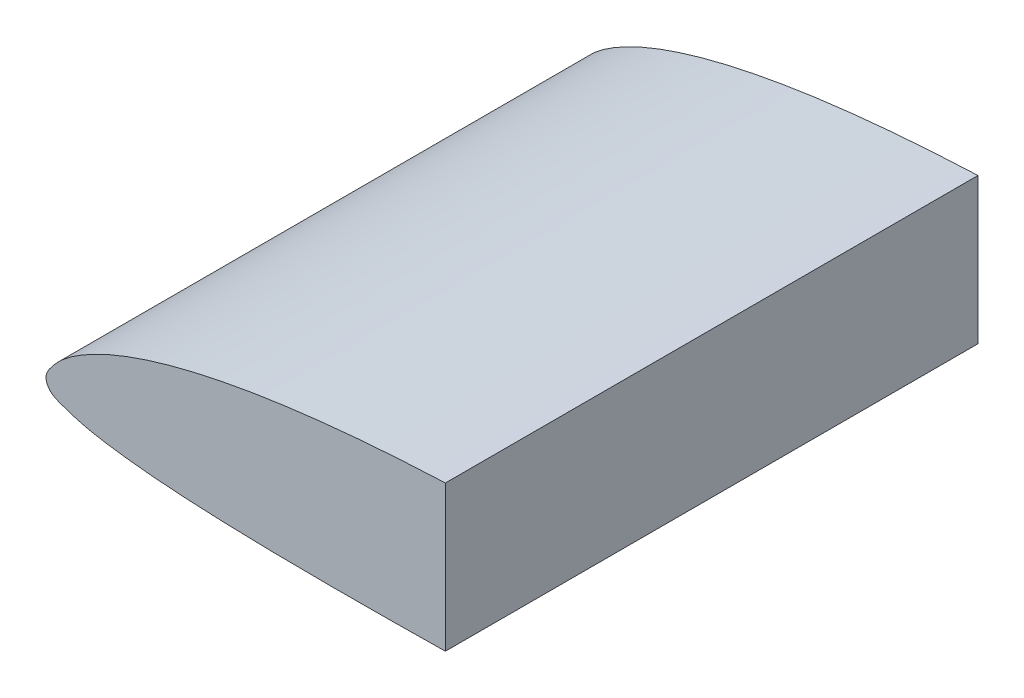
SolidWorks part; units mm, degrees
ref_plane "Front Plane" through (0, 0, 0) normal (0, 0, 1) x (1, 0, 0)
ref_plane "Top Plane" through (0, 0, 0) normal (0, 1, 0) x (1, 0, 0)
ref_plane "Right Plane" through (0, 0, 0) normal (1, 0, 0) x (0, 0, -1)
curve "Curve1"
  spline degree 3 poles (302.6596, 0.1157, 0) (305.3381, -0.0423, 0) (302.669, 0.2207, 0) (300.522, 0.5446, 0) (295.3689, 1.2875, 0) (289.1609, 2.3365, 0) (281.2138, 3.7195, 0) (272.0211, 5.3425, 0) (261.6111, 7.1258, 0) (250.1482, 8.9723, 0) (237.7292, 10.7955, 0) (224.4667, 12.5459, 0) (210.487, 14.2121, 0) (195.9393, 15.7786, 0) (180.9854, 17.2135, 0) (165.7905, 18.4813, 0) (150.5173, 19.555, 0) (135.3259, 20.3976, 0) (120.3737, 20.9834, 0) (105.8119, 21.2902, 0) (91.7835, 21.2891, 0) (78.4214, 20.9725, 0) (65.8465, 20.3288, 0) (54.1674, 19.3419, 0) (43.4744, 18.033, 0) (33.8487, 16.4082, 0) (25.3526, 14.4995, 0) (18.0396, 12.3489, 0) (11.9314, 10.004, 0) (7.0881, 7.5397, 0) (3.4097, 5.063, 0) (1.1505, 2.6895, 0) (-0.3415, 0.4062, 0) (0.6752, -2.0035, 0) (3.5859, -3.0935, 0) (7.5885, -4.3543, 0) (13.2868, -5.2878, 0) (20.4322, -6.0839, 0) (29.0602, -6.6397, 0) (39.0679, -6.9954, 0) (50.3738, -7.1553, 0) (62.8573, -7.1477, 0) (76.3839, -6.9932, 0) (90.8032, -6.6986, 0) (105.9568, -6.2837, 0) (121.6773, -5.7705, 0) (137.79, -5.1759, 0) (154.1149, -4.5178, 0) (170.47, -3.8155, 0) (186.6709, -3.1003, 0) (202.5321, -2.3909, 0) (217.8684, -1.7248, 0) (232.4928, -1.115, 0) (246.2209, -0.6139, 0) (258.8615, -0.2157, 0) (270.2531, 0.0554, 0) (280.189, 0.2196, 0) (288.6505, 0.2748, 0) (295.1556, 0.2617, 0) (300.4646, 0.1437, 0) (302.6596, 0.1157, 0) (305.3381, -0.0423, 0) (302.669, 0.2207, 0) knots -0.014411 -0.006469 -0.001624 0 0.001633 0.006456 0.014273 0.024844 0.037882 0.053108 0.070262 0.089112 0.109474 0.131183 0.154044 0.177808 0.202202 0.22696 0.251816 0.276516 0.300807 0.324444 0.347208 0.368894 0.389314 0.408315 0.425773 0.441588 0.45568 0.468012 0.478567 0.487363 0.494419 0.499795 0.503598 0.50652 0.511061 0.517924 0.527205 0.538874 0.552882 0.569133 0.587486 0.607759 0.629726 0.653145 0.677762 0.703306 0.729491 0.756024 0.782609 0.80895 0.834737 0.859675 0.88346 0.905785 0.926349 0.944858 0.961055 0.974701 0.985589 0.993531 0.998376 1 1.001633 1.006456 1.014273 periodic
sketch "Sketch1" plane through (0, 0, 0) normal (0, 0, 1) x (1, 0, 0)
  line L2 (0, 0) -> (0, 1.9929) construction
  spline S1 degree 3 poles (302.6596, 0.1157) (305.3381, -0.0423) (302.669, 0.2207) (300.522, 0.5446) (295.3689, 1.2875) (289.1609, 2.3365) (281.2138, 3.7195) (272.0211, 5.3425) (261.6111, 7.1258) (250.1482, 8.9723) (237.7292, 10.7955) (224.4667, 12.5459) (210.487, 14.2121) (195.9393, 15.7786) (180.9854, 17.2135) (165.7905, 18.4813) (150.5173, 19.555) (135.3259, 20.3976) (120.3737, 20.9834) (105.8119, 21.2902) (91.7835, 21.2891) (78.4214, 20.9725) (65.8465, 20.3288) (54.1674, 19.3419) (43.4744, 18.033) (33.8487, 16.4082) (25.3526, 14.4995) (18.0396, 12.3489) (11.9314, 10.004) (7.0881, 7.5397) (3.4097, 5.063) (1.1505, 2.6895) (-0.3415, 0.4062) (0.6752, -2.0035) (3.5859, -3.0935) (7.5885, -4.3543) (13.2868, -5.2878) (20.4322, -6.0839) (29.0602, -6.6397) (39.0679, -6.9954) (50.3738, -7.1553) (62.8573, -7.1477) (76.3839, -6.9932) (90.8032, -6.6986) (105.9568, -6.2837) (121.6773, -5.7705) (137.79, -5.1759) (154.1149, -4.5178) (170.47, -3.8155) (186.6709, -3.1003) (202.5321, -2.3909) (217.8684, -1.7248) (232.4928, -1.115) (246.2209, -0.6139) (258.8615, -0.2157) (270.2531, 0.0554) (280.189, 0.2196) (288.6505, 0.2748) (295.1556, 0.2617) (300.4646, 0.1437) (302.6596, 0.1157) (305.3381, -0.0423) (302.669, 0.2207) knots -0.014411 -0.006469 -0.001624 0 0.001633 0.006456 0.014273 0.024844 0.037882 0.053108 0.070262 0.089112 0.109474 0.131183 0.154044 0.177808 0.202202 0.22696 0.251816 0.276516 0.300807 0.324444 0.347208 0.368894 0.389314 0.408315 0.425773 0.441588 0.45568 0.468012 0.478567 0.487363 0.494419 0.499795 0.503598 0.50652 0.511061 0.517924 0.527205 0.538874 0.552882 0.569133 0.587486 0.607759 0.629726 0.653145 0.677762 0.703306 0.729491 0.756024 0.782609 0.80895 0.834737 0.859675 0.88346 0.905785 0.926349 0.944858 0.961055 0.974701 0.985589 0.993531 0.998376 1 1.001633 1.006456 1.014273 only from (304.8, 0) to (304.8, 0) construction
  spline S2 degree 3 poles (302.6596, 0.1157) (305.3381, -0.0423) (302.669, 0.2207) (300.522, 0.5446) (295.3689, 1.2875) (289.1609, 2.3365) (281.2138, 3.7195) (272.0211, 5.3425) (261.6111, 7.1258) (250.1482, 8.9723) (237.7292, 10.7955) (224.4667, 12.5459) (210.487, 14.2121) (195.9393, 15.7786) (180.9854, 17.2135) (165.7905, 18.4813) (150.5173, 19.555) (135.3259, 20.3976) (120.3737, 20.9834) (105.8119, 21.2902) (91.7835, 21.2891) (78.4214, 20.9725) (65.8465, 20.3288) (54.1674, 19.3419) (43.4744, 18.033) (33.8487, 16.4082) (25.3526, 14.4995) (18.0396, 12.3489) (11.9314, 10.004) (7.0881, 7.5397) (3.4097, 5.063) (1.1505, 2.6895) (-0.3415, 0.4062) (0.6752, -2.0035) (3.5859, -3.0935) (7.5885, -4.3543) (13.2868, -5.2878) (20.4322, -6.0839) (29.0602, -6.6397) (39.0679, -6.9954) (50.3738, -7.1553) (62.8573, -7.1477) (76.3839, -6.9932) (90.8032, -6.6986) (105.9568, -6.2837) (121.6773, -5.7705) (137.79, -5.1759) (154.1149, -4.5178) (170.47, -3.8155) (186.6709, -3.1003) (202.5321, -2.3909) (217.8684, -1.7248) (232.4928, -1.115) (246.2209, -0.6139) (258.8615, -0.2157) (270.2531, 0.0554) (280.189, 0.2196) (288.6505, 0.2748) (295.1556, 0.2617) (300.4646, 0.1437) (302.6596, 0.1157) (305.3381, -0.0423) (302.669, 0.2207) knots -0.014411 -0.006469 -0.001624 0 0.001633 0.006456 0.014273 0.024844 0.037882 0.053108 0.070262 0.089112 0.109474 0.131183 0.154044 0.177808 0.202202 0.22696 0.251816 0.276516 0.300807 0.324444 0.347208 0.368894 0.389314 0.408315 0.425773 0.441588 0.45568 0.468012 0.478567 0.487363 0.494419 0.499795 0.503598 0.50652 0.511061 0.517924 0.527205 0.538874 0.552882 0.569133 0.587486 0.607759 0.629726 0.653145 0.677762 0.703306 0.729491 0.756024 0.782609 0.80895 0.834737 0.859675 0.88346 0.905785 0.926349 0.944858 0.961055 0.974701 0.985589 0.993531 0.998376 1 1.001633 1.006456 1.014273 only from (304.8, 0) to (304.8, 0)
extrude "Boss-Extrude1" add sketch "Sketch1" along normal blind 101.6
sketch "Sketch2" plane through (0, 0, 101.6) normal (0, 0, 1) x (1, 0, 0)
  line L0 (76.2, 20.8248) -> (76.2, -6.975)
  spline S0 degree 3 poles (302.6596, 0.1157) (305.3381, -0.0423) (302.669, 0.2207) (300.522, 0.5446) (295.3689, 1.2875) (289.1609, 2.3365) (281.2138, 3.7195) (272.0211, 5.3425) (261.6111, 7.1258) (250.1482, 8.9723) (237.7292, 10.7955) (224.4667, 12.5459) (210.487, 14.2121) (195.9393, 15.7786) (180.9854, 17.2135) (165.7905, 18.4813) (150.5173, 19.555) (135.3259, 20.3976) (120.3737, 20.9834) (105.8119, 21.2902) (91.7835, 21.2891) (78.4214, 20.9725) (65.8465, 20.3288) (54.1674, 19.3419) (43.4744, 18.033) (33.8487, 16.4082) (25.3526, 14.4995) (18.0396, 12.3489) (11.9314, 10.004) (7.0881, 7.5397) (3.4097, 5.063) (1.1505, 2.6895) (-0.3415, 0.4062) (0.6752, -2.0035) (3.5859, -3.0935) (7.5885, -4.3543) (13.2868, -5.2878) (20.4322, -6.0839) (29.0602, -6.6397) (39.0679, -6.9954) (50.3738, -7.1553) (62.8573, -7.1477) (76.3839, -6.9932) (90.8032, -6.6986) (105.9568, -6.2837) (121.6773, -5.7705) (137.79, -5.1759) (154.1149, -4.5178) (170.47, -3.8155) (186.6709, -3.1003) (202.5321, -2.3909) (217.8684, -1.7248) (232.4928, -1.115) (246.2209, -0.6139) (258.8615, -0.2157) (270.2531, 0.0554) (280.189, 0.2196) (288.6505, 0.2748) (295.1556, 0.2617) (300.4646, 0.1437) (302.6596, 0.1157) (305.3381, -0.0423) (302.669, 0.2207) knots -0.014411 -0.006469 -0.001624 0 0.001633 0.006456 0.014273 0.024844 0.037882 0.053108 0.070262 0.089112 0.109474 0.131183 0.154044 0.177808 0.202202 0.22696 0.251816 0.276516 0.300807 0.324444 0.347208 0.368894 0.389314 0.408315 0.425773 0.441588 0.45568 0.468012 0.478567 0.487363 0.494419 0.499795 0.503598 0.50652 0.511061 0.517924 0.527205 0.538874 0.552882 0.569133 0.587486 0.607759 0.629726 0.653145 0.677762 0.703306 0.729491 0.756024 0.782609 0.80895 0.834737 0.859675 0.88346 0.905785 0.926349 0.944858 0.961055 0.974701 0.985589 0.993531 0.998376 1 1.001633 1.006456 1.014273 only from (304.8, 0) to (304.8, 0) construction
  spline S1 degree 3 poles (302.6596, 0.1157) (305.3381, -0.0423) (302.669, 0.2207) (300.522, 0.5446) (295.3689, 1.2875) (289.1609, 2.3365) (281.2138, 3.7195) (272.0211, 5.3425) (261.6111, 7.1258) (250.1482, 8.9723) (237.7292, 10.7955) (224.4667, 12.5459) (210.487, 14.2121) (195.9393, 15.7786) (180.9854, 17.2135) (165.7905, 18.4813) (150.5173, 19.555) (135.3259, 20.3976) (120.3737, 20.9834) (105.8119, 21.2902) (91.7835, 21.2891) (78.4214, 20.9725) (65.8465, 20.3288) (54.1674, 19.3419) (43.4744, 18.033) (33.8487, 16.4082) (25.3526, 14.4995) (18.0396, 12.3489) (11.9314, 10.004) (7.0881, 7.5397) (3.4097, 5.063) (1.1505, 2.6895) (-0.3415, 0.4062) (0.6752, -2.0035) (3.5859, -3.0935) (7.5885, -4.3543) (13.2868, -5.2878) (20.4322, -6.0839) (29.0602, -6.6397) (39.0679, -6.9954) (50.3738, -7.1553) (62.8573, -7.1477) (76.3839, -6.9932) (90.8032, -6.6986) (105.9568, -6.2837) (121.6773, -5.7705) (137.79, -5.1759) (154.1149, -4.5178) (170.47, -3.8155) (186.6709, -3.1003) (202.5321, -2.3909) (217.8684, -1.7248) (232.4928, -1.115) (246.2209, -0.6139) (258.8615, -0.2157) (270.2531, 0.0554) (280.189, 0.2196) (288.6505, 0.2748) (295.1556, 0.2617) (300.4646, 0.1437) (302.6596, 0.1157) (305.3381, -0.0423) (302.669, 0.2207) knots -0.014411 -0.006469 -0.001624 0 0.001633 0.006456 0.014273 0.024844 0.037882 0.053108 0.070262 0.089112 0.109474 0.131183 0.154044 0.177808 0.202202 0.22696 0.251816 0.276516 0.300807 0.324444 0.347208 0.368894 0.389314 0.408315 0.425773 0.441588 0.45568 0.468012 0.478567 0.487363 0.494419 0.499795 0.503598 0.50652 0.511061 0.517924 0.527205 0.538874 0.552882 0.569133 0.587486 0.607759 0.629726 0.653145 0.677762 0.703306 0.729491 0.756024 0.782609 0.80895 0.834737 0.859675 0.88346 0.905785 0.926349 0.944858 0.961055 0.974701 0.985589 0.993531 0.998376 1 1.001633 1.006456 1.014273 only from (304.8, 0) to (304.8, 0)
  spline S2 degree 3 poles (302.6596, 0.1157) (305.3381, -0.0423) (302.669, 0.2207) (300.522, 0.5446) (295.3689, 1.2875) (289.1609, 2.3365) (281.2138, 3.7195) (272.0211, 5.3425) (261.6111, 7.1258) (250.1482, 8.9723) (237.7292, 10.7955) (224.4667, 12.5459) (210.487, 14.2121) (195.9393, 15.7786) (180.9854, 17.2135) (165.7905, 18.4813) (150.5173, 19.555) (135.3259, 20.3976) (120.3737, 20.9834) (105.8119, 21.2902) (91.7835, 21.2891) (78.4214, 20.9725) (65.8465, 20.3288) (54.1674, 19.3419) (43.4744, 18.033) (33.8487, 16.4082) (25.3526, 14.4995) (18.0396, 12.3489) (11.9314, 10.004) (7.0881, 7.5397) (3.4097, 5.063) (1.1505, 2.6895) (-0.3415, 0.4062) (0.6752, -2.0035) (3.5859, -3.0935) (7.5885, -4.3543) (13.2868, -5.2878) (20.4322, -6.0839) (29.0602, -6.6397) (39.0679, -6.9954) (50.3738, -7.1553) (62.8573, -7.1477) (76.3839, -6.9932) (90.8032, -6.6986) (105.9568, -6.2837) (121.6773, -5.7705) (137.79, -5.1759) (154.1149, -4.5178) (170.47, -3.8155) (186.6709, -3.1003) (202.5321, -2.3909) (217.8684, -1.7248) (232.4928, -1.115) (246.2209, -0.6139) (258.8615, -0.2157) (270.2531, 0.0554) (280.189, 0.2196) (288.6505, 0.2748) (295.1556, 0.2617) (300.4646, 0.1437) (302.6596, 0.1157) (305.3381, -0.0423) (302.669, 0.2207) knots -0.014411 -0.006469 -0.001624 0 0.001633 0.006456 0.014273 0.024844 0.037882 0.053108 0.070262 0.089112 0.109474 0.131183 0.154044 0.177808 0.202202 0.22696 0.251816 0.276516 0.300807 0.324444 0.347208 0.368894 0.389314 0.408315 0.425773 0.441588 0.45568 0.468012 0.478567 0.487363 0.494419 0.499795 0.503598 0.50652 0.511061 0.517924 0.527205 0.538874 0.552882 0.569133 0.587486 0.607759 0.629726 0.653145 0.677762 0.703306 0.729491 0.756024 0.782609 0.80895 0.834737 0.859675 0.88346 0.905785 0.926349 0.944858 0.961055 0.974701 0.985589 0.993531 0.998376 1 1.001633 1.006456 1.014273 only from (304.8, 0) to (304.8, 0)
  spline S3 degree 3 poles (302.6596, 0.1157) (305.3381, -0.0423) (302.669, 0.2207) (300.522, 0.5446) (295.3689, 1.2875) (289.1609, 2.3365) (281.2138, 3.7195) (272.0211, 5.3425) (261.6111, 7.1258) (250.1482, 8.9723) (237.7292, 10.7955) (224.4667, 12.5459) (210.487, 14.2121) (195.9393, 15.7786) (180.9854, 17.2135) (165.7905, 18.4813) (150.5173, 19.555) (135.3259, 20.3976) (120.3737, 20.9834) (105.8119, 21.2902) (91.7835, 21.2891) (78.4214, 20.9725) (65.8465, 20.3288) (54.1674, 19.3419) (43.4744, 18.033) (33.8487, 16.4082) (25.3526, 14.4995) (18.0396, 12.3489) (11.9314, 10.004) (7.0881, 7.5397) (3.4097, 5.063) (1.1505, 2.6895) (-0.3415, 0.4062) (0.6752, -2.0035) (3.5859, -3.0935) (7.5885, -4.3543) (13.2868, -5.2878) (20.4322, -6.0839) (29.0602, -6.6397) (39.0679, -6.9954) (50.3738, -7.1553) (62.8573, -7.1477) (76.3839, -6.9932) (90.8032, -6.6986) (105.9568, -6.2837) (121.6773, -5.7705) (137.79, -5.1759) (154.1149, -4.5178) (170.47, -3.8155) (186.6709, -3.1003) (202.5321, -2.3909) (217.8684, -1.7248) (232.4928, -1.115) (246.2209, -0.6139) (258.8615, -0.2157) (270.2531, 0.0554) (280.189, 0.2196) (288.6505, 0.2748) (295.1556, 0.2617) (300.4646, 0.1437) (302.6596, 0.1157) (305.3381, -0.0423) (302.669, 0.2207) knots -0.014411 -0.006469 -0.001624 0 0.001633 0.006456 0.014273 0.024844 0.037882 0.053108 0.070262 0.089112 0.109474 0.131183 0.154044 0.177808 0.202202 0.22696 0.251816 0.276516 0.300807 0.324444 0.347208 0.368894 0.389314 0.408315 0.425773 0.441588 0.45568 0.468012 0.478567 0.487363 0.494419 0.499795 0.503598 0.50652 0.511061 0.517924 0.527205 0.538874 0.552882 0.569133 0.587486 0.607759 0.629726 0.653145 0.677762 0.703306 0.729491 0.756024 0.782609 0.80895 0.834737 0.859675 0.88346 0.905785 0.926349 0.944858 0.961055 0.974701 0.985589 0.993531 0.998376 1 1.001633 1.006456 1.014273 only from (304.8, 0) to (304.8, 0) construction
  dimension "D2" = 76.2
  dimension "D1" = 0
extrude "Cut-Extrude1" cut sketch "Sketch2" against normal up to surface (101.6 mm away)
